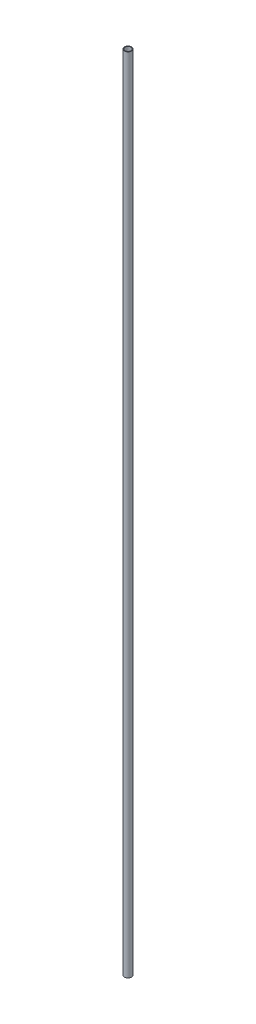
SolidWorks part; units mm, degrees
material "AISI 316 Stainless Steel Sheet (SS)"
ref_plane "Front Plane" through (0, 0, 0) normal (0, 0, 1) x (1, 0, 0)
ref_plane "Top Plane" through (0, 0, 0) normal (0, 1, 0) x (1, 0, 0)
ref_plane "Right Plane" through (0, 0, 0) normal (1, 0, 0) x (0, 0, -1)
sketch "Sketch1" plane through (0, 0, 0) normal (0, 1, 0) x (1, 0, 0)
  circle A0 centre (0, 0) radius 6.35
  circle A1 centre (0, 0) radius 5.35
  dimension "D1" = 12.7
  dimension "D2" = 1
extrude "Boss-Extrude1" add sketch "Sketch1" along normal blind 1419.5
